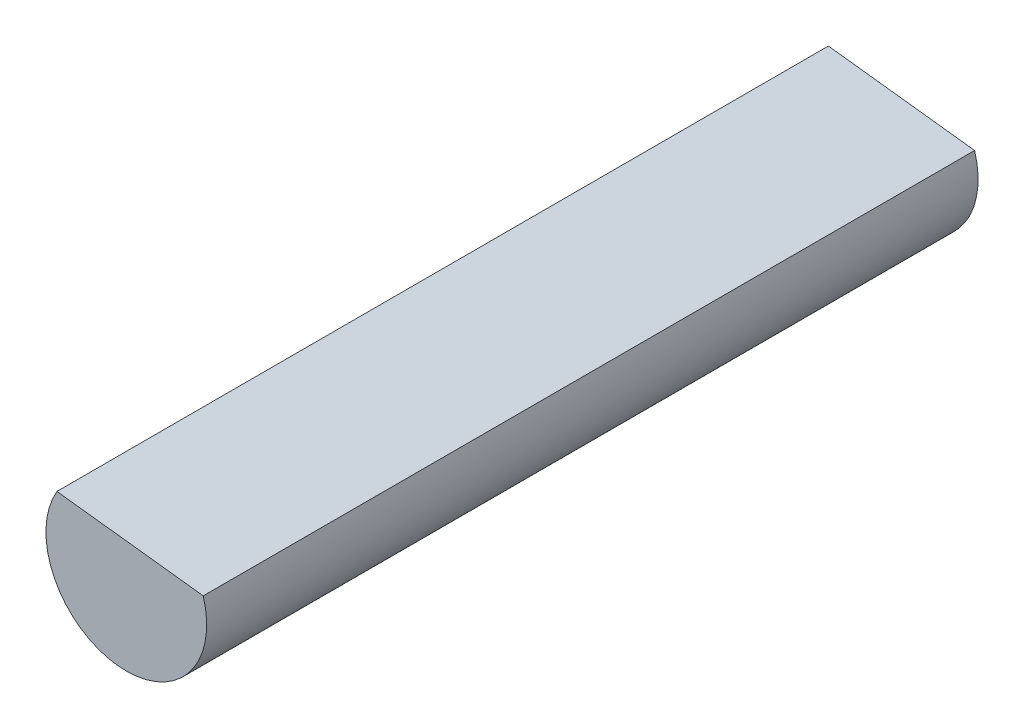
SolidWorks part; units mm, degrees
ref_plane "前视基准面" through (0, 0, 0) normal (0, 0, 1) x (1, 0, 0)
ref_plane "上视基准面" through (0, 0, 0) normal (0, 1, 0) x (1, 0, 0)
ref_plane "右视基准面" through (0, 0, 0) normal (1, 0, 0) x (0, 0, -1)
other "Configuration Table"
sketch "草图1" plane through (0, 0, 0) normal (0, 0, 1) x (1, 0, 0)
  line L0 (4.7859, 1.4475) -> (-4.3157, 2.5248)
  arc A0 (-4.3157, 2.5248) -> (4.7859, 1.4475) centre (0, 0) ccw
extrude "凸台-拉伸1" add sketch "草图1" along normal blind 48
